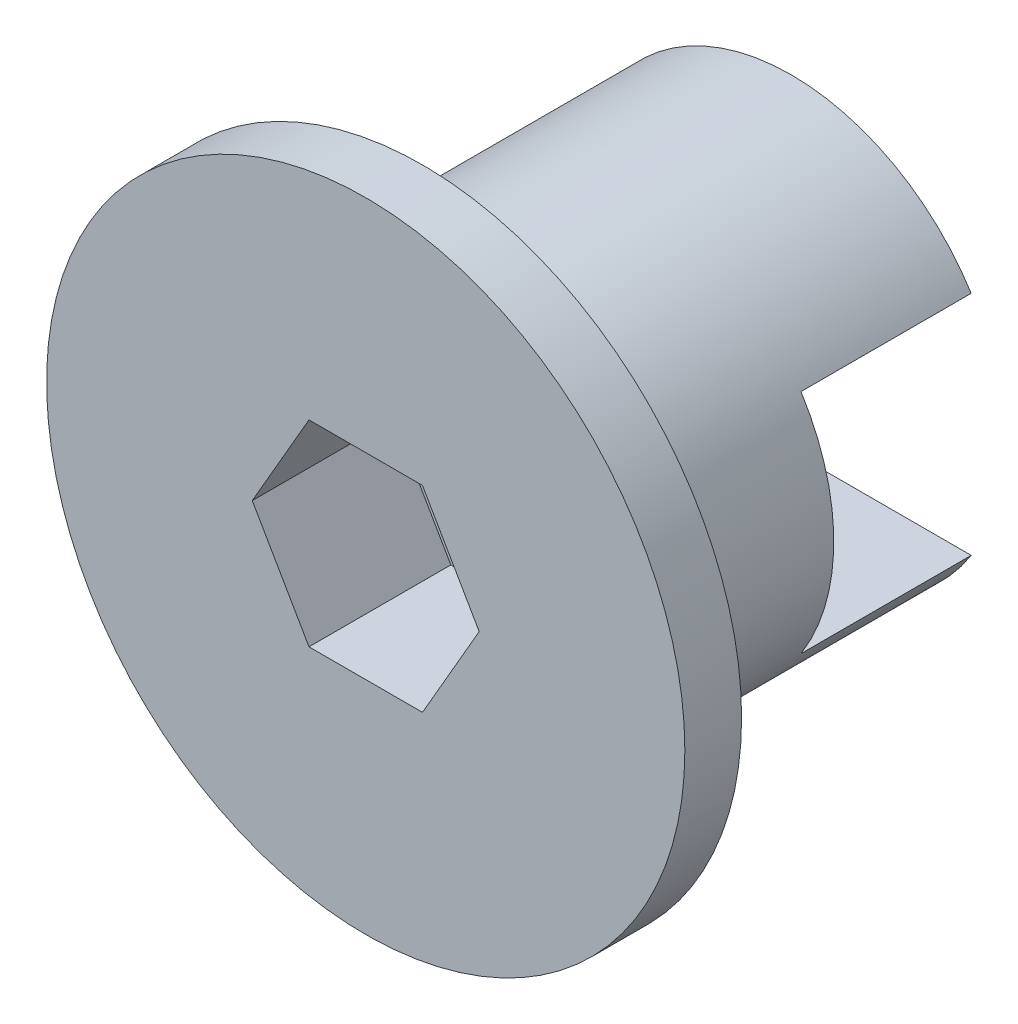
SolidWorks part; units mm, degrees
ref_plane "Front Plane" through (0, 0, 0) normal (0, 0, 1) x (1, 0, 0)
ref_plane "Top Plane" through (0, 0, 0) normal (0, 1, 0) x (1, 0, 0)
ref_plane "Right Plane" through (0, 0, 0) normal (1, 0, 0) x (0, 0, -1)
sketch "Sketch1" plane through (0, 0, 0) normal (0, 0, 1) x (1, 0, 0)
  circle A0 centre (0, 0) radius 15
  circle A1 centre (0, 0) radius 5
  dimension "D1" = 30
  dimension "D2" = 10
extrude "Boss-Extrude1" add sketch "Sketch1" along normal blind 30
sketch "Sketch2" plane through (0, 0, 30) normal (0, 0, 1) x (1, 0, 0)
  line L1 (8, 0) -> (4, 6.9282)
  line L2 (4, 6.9282) -> (-4, 6.9282)
  line L3 (-4, 6.9282) -> (-8, 0)
  line L4 (-8, 0) -> (-4, -6.9282)
  line L5 (-4, -6.9282) -> (4, -6.9282)
  line L6 (4, -6.9282) -> (8, 0)
  circle A0 centre (0, 0) radius 6.9282 construction
  dimension "D1" = 16
extrude "Cut-Extrude1" cut sketch "Sketch2" against normal blind 10
sketch "Sketch3" plane through (0, 0, 0) normal (1, 0, 0) x (0, 0, -1)
  line L0 (0, -15) -> (0, 15) construction
  line L1 (0, 8) -> (-12, 8)
  line L2 (0, 8) -> (0, -8)
  line L3 (0, -8) -> (-12, -8)
  line L4 (-12, 8) -> (-12, -8)
  point P6 (-12, 0)
  dimension "D1" = 16
  dimension "D2" = 12
extrude "Cut-Extrude2" cut sketch "Sketch3" against normal through all and the other way through all
sketch "Sketch4" plane through (0, 0, 30) normal (0, 0, 1) x (1, 0, 0)
  circle A0 centre (0, 0) radius 15 construction
  circle A1 centre (0, 0) radius 15
  circle A2 centre (0, 0) radius 22.5
  dimension "D1" = 45
extrude "Boss-Extrude2" add sketch "Sketch4" against normal blind 4
